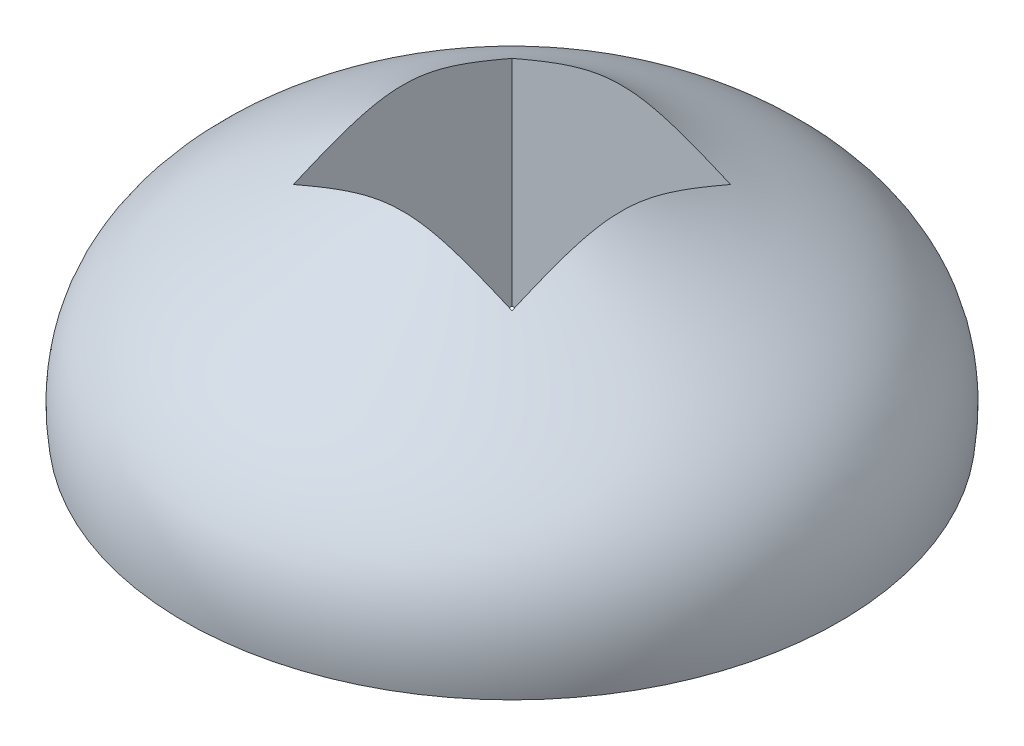
SolidWorks part; units mm, degrees
ref_plane "Front Plane" through (0, 0, 0) normal (0, 0, 1) x (1, 0, 0)
ref_plane "Top Plane" through (0, 0, 0) normal (0, 1, 0) x (1, 0, 0)
ref_plane "Right Plane" through (0, 0, 0) normal (1, 0, 0) x (0, 0, -1)
sketch "Sketch1" plane through (0, 0, 0) normal (0, 0, 1) x (1, 0, 0)
  line L0 (0, 0) -> (0, 0.5)
  line L1 (0, 0) -> (0.6, 0)
  line L2 (0, 0.5) -> (0.15, 0.5)
  spline S0 degree 3 poles (0.15, 0.5) (0.2943, 0.3247) (0.6411, 0.3022) (0.6, 0) knots 0 0 0 0 1 1 1 1
  point P5 (0.2469, 0.421)
  point P8 (0.3291, 0.3657)
  dimension "D1" = 0.6
  dimension "D2" = 0.5
  dimension "D3" = 0.15
revolve "Revolve1" add sketch "Sketch1" angle 360 about L0
sketch "Sketch2" plane through (0, 0, 0) normal (0, -1, 0) x (1, 0, 0)
  line L1 (-0.2, -0.2) -> (0.2, -0.2)
  line L2 (-0.2, -0.2) -> (-0.2, 0.2)
  line L3 (-0.2, 0.2) -> (0.2, 0.2)
  line L4 (0.2, -0.2) -> (0.2, 0.2)
  line L5 (-0.2, -0.2) -> (0.2, 0.2) construction
  line L6 (-0.2, 0.2) -> (0.2, -0.2) construction
  point P0 (0, 0)
  dimension "D1" = 0.4
extrude "Cut-Extrude1" cut sketch "Sketch2" against normal through all
